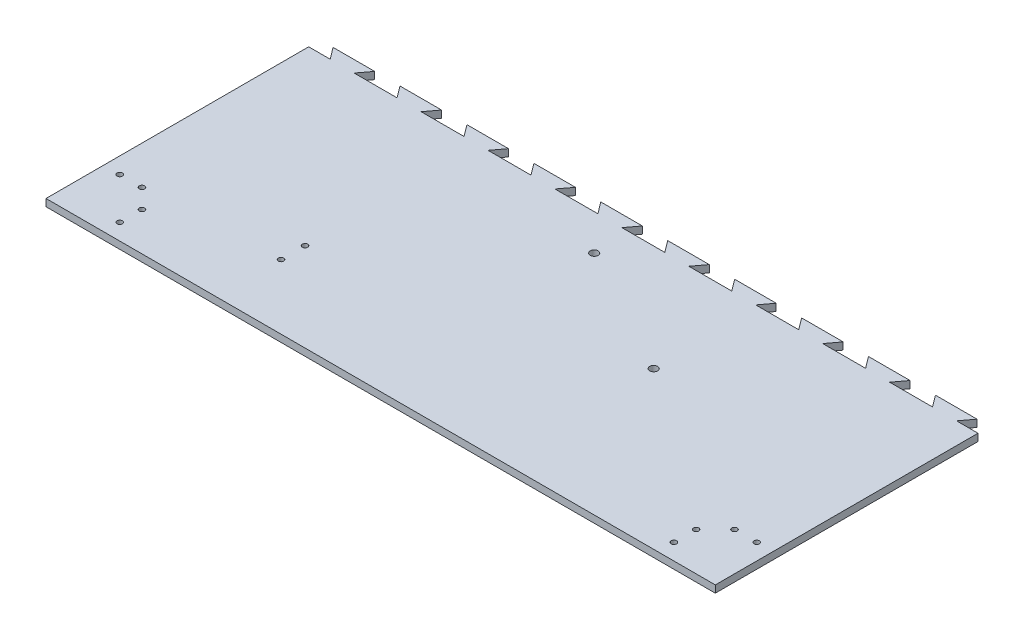
SolidWorks part; units mm, degrees
material "Multistrato di pioppo"
ref_plane "Piano frontale" through (0, 0, 0) normal (0, 0, 1) x (1, 0, 0)
ref_plane "Piano superiore" through (0, 0, 0) normal (0, 1, 0) x (1, 0, 0)
ref_plane "Piano destro" through (0, 0, 0) normal (1, 0, 0) x (0, 0, -1)
sketch "Schizzo1" plane through (0, 0, 0) normal (0, 1, 0) x (1, 0, 0)
  line L1 (-279, 219) -> (279, 219)
  line L2 (-279, 219) -> (-279, -219)
  line L3 (-279, -219) -> (279, -219)
  line L4 (279, 219) -> (279, -219)
  line L5 (-279, 219) -> (279, -219) construction
  line L6 (-279, -219) -> (279, 219) construction
  point P4 (0, 0)
  dimension "D1" = 558
  dimension "D2" = 438
extrude "Estrusione-Estrusione1" add sketch "Schizzo1" along normal blind 6
sketch "Schizzo2" plane through (0, 6, 0) normal (0, 1, 0) x (1, 0, 0)
  circle A0 centre (-231, 205.5) radius 2.25
  circle A1 centre (-231, 187) radius 2.25
  circle A2 centre (-247, 171) radius 2.25
  circle A3 centre (-265.5, 171) radius 2.25
  circle A4 centre (231, 205.5) radius 2.25
  circle A5 centre (231, 187) radius 2.25
  circle A6 centre (247, 171) radius 2.25
  circle A7 centre (265.5, 171) radius 2.25
  circle A8 centre (265.5, -171) radius 2.25
  circle A9 centre (247, -171) radius 2.25
  circle A10 centre (231, -187) radius 2.25
  circle A11 centre (231, -205.5) radius 2.25
  circle A12 centre (-231, -205.5) radius 2.25
  circle A13 centre (-231, -187) radius 2.25
  circle A14 centre (-247, -171) radius 2.25
  circle A15 centre (-265.5, -171) radius 2.25
  dimension "D1" = 4.5
extrude "Taglio-Estrusione1" cut sketch "Schizzo2" against normal blind 10
sketch "Schizzo4" plane through (0, 6, 0) normal (0, 1, 0) x (1, 0, 0)
  line L0 (279, -219) -> (279, 219) construction
  line L1 (279, 219) -> (-279, 219) construction
  line L2 (-279, -219) -> (279, -219) construction
  line L3 (-279, 219) -> (-279, -219) construction
  line L4 (-11.0471, -29.9509) -> (72.3592, -5.1397) construction
  line L5 (72.3592, -5.1397) -> (47.5479, 78.2666) construction
  line L6 (72.3592, -5.1397) -> (97.1704, -88.546) construction
  circle A0 centre (-11.0471, -29.9509) radius 3.3
  circle A1 centre (97.1704, -88.546) radius 3.3
  circle A2 centre (155.7655, 19.6716) radius 3.3
  circle A3 centre (47.5479, 78.2666) radius 3.3
  circle A4 centre (72.3592, -5.1397) radius 87.0184 construction
  dimension "D1" = 6.6
  dimension "D3" = 199.3284
  dimension "D4" = 174.0369
  dimension "D2" = 123.2345
  dimension "D5" = 189.0491
  dimension "D6" = 267.9529
  dimension "D7" = 90
extrude "Taglio-Estrusione2" cut sketch "Schizzo4" against normal blind 10
sketch "Schizzo5" plane through (0, 0, 0) normal (0, -1, 0) x (1, 0, 0)
  line L0 (-279, -219) -> (-279, 219) construction
  line L1 (-279, 219) -> (279, 219) construction
  line L2 (-136.9216, 165.1352) -> (-136.9216, 145.1352) construction
  circle A2 centre (-136.9216, 165.1352) radius 2.25
  circle A3 centre (-136.9216, 145.1352) radius 2.25
  dimension "D4" = 4.5
  dimension "D1" = 20
  dimension "D2" = 142.0784
  dimension "D3" = 73.8648
extrude "Taglio-Estrusione3" cut sketch "Schizzo5" against normal blind 10
sketch "Schizzo6" plane through (0, 6, 0) normal (0, 1, 0) x (1, 0, 0)
  line L0 (-279, 0) -> (-261.1, 0)
  line L1 (-268.4125, 9.75) -> (-233.7875, 9.75)
  line L2 (-261.1, 0) -> (-268.4125, 9.75)
  line L3 (-279, 219) -> (-279, -219) construction
  line L4 (-261.1, 0) -> (-268.6, 10) construction
  line L5 (-268.6, 10) -> (-233.6, 10) construction
  line L6 (-233.6, 10) -> (-241.1, 0) construction
  line L7 (-241.1, 0) -> (-223.2, 0)
  line L8 (-261.1, 0) -> (-241.1, 0) construction
  line L9 (-251.1, 0) -> (-251.1, 10) construction
  line L10 (-241.1, 0) -> (-233.7875, 9.75)
  line L11 (-223.2, 0) -> (-205.3, 0)
  line L12 (-205.3, 0) -> (-212.6125, 9.75)
  line L13 (-212.6125, 9.75) -> (-177.9875, 9.75)
  line L14 (-185.3, 0) -> (-177.9875, 9.75)
  line L15 (-185.3, 0) -> (-167.4, 0)
  line L16 (-167.4, 0) -> (-149.5, 0)
  line L17 (-149.5, 0) -> (-156.8125, 9.75)
  line L18 (-156.8125, 9.75) -> (-122.1875, 9.75)
  line L19 (-129.5, 0) -> (-122.1875, 9.75)
  line L20 (-129.5, 0) -> (-111.6, 0)
  line L21 (-111.6, 0) -> (-93.7, 0)
  line L22 (-93.7, 0) -> (-101.0125, 9.75)
  line L23 (-101.0125, 9.75) -> (-66.3875, 9.75)
  line L24 (-73.7, 0) -> (-66.3875, 9.75)
  line L25 (-73.7, 0) -> (-55.8, 0)
  line L26 (-55.8, 0) -> (-37.9, 0)
  line L27 (-37.9, 0) -> (-45.2125, 9.75)
  line L28 (-45.2125, 9.75) -> (-10.5875, 9.75)
  line L29 (-17.9, 0) -> (-10.5875, 9.75)
  line L30 (-17.9, 0) -> (0, 0)
  line L31 (0, 0) -> (17.9, 0)
  line L32 (17.9, 0) -> (10.5875, 9.75)
  line L33 (10.5875, 9.75) -> (45.2125, 9.75)
  line L34 (37.9, 0) -> (45.2125, 9.75)
  line L35 (37.9, 0) -> (55.8, 0)
  line L36 (55.8, 0) -> (73.7, 0)
  line L37 (73.7, 0) -> (66.3875, 9.75)
  line L38 (66.3875, 9.75) -> (101.0125, 9.75)
  line L39 (93.7, 0) -> (101.0125, 9.75)
  line L40 (93.7, 0) -> (111.6, 0)
  line L41 (111.6, 0) -> (129.5, 0)
  line L42 (129.5, 0) -> (122.1875, 9.75)
  line L43 (122.1875, 9.75) -> (156.8125, 9.75)
  line L44 (149.5, 0) -> (156.8125, 9.75)
  line L45 (149.5, 0) -> (167.4, 0)
  line L46 (167.4, 0) -> (185.3, 0)
  line L47 (185.3, 0) -> (177.9875, 9.75)
  line L48 (177.9875, 9.75) -> (212.6125, 9.75)
  line L49 (205.3, 0) -> (212.6125, 9.75)
  line L50 (205.3, 0) -> (223.2, 0)
  line L51 (223.2, 0) -> (241.1, 0)
  line L52 (241.1, 0) -> (233.7875, 9.75)
  line L53 (233.7875, 9.75) -> (268.4125, 9.75)
  line L54 (261.1, 0) -> (268.4125, 9.75)
  line L55 (261.1, 0) -> (279, 0)
  line L56 (279, -219) -> (279, 219) construction
  line L57 (-279, 0) -> (-279, 219)
  line L58 (-279, 219) -> (279, 219)
  line L59 (279, 219) -> (279, 0)
  point P15 (-251.1, 9.75)
  dimension "D1" = 55.8
  dimension "D2" = 10
  dimension "D3" = 35
  dimension "D4" = 20
  dimension "D5" = 0.5
  dimension "D6" = 10
extrude "Taglio-Estrusione4" cut sketch "Schizzo6" against normal blind 10
